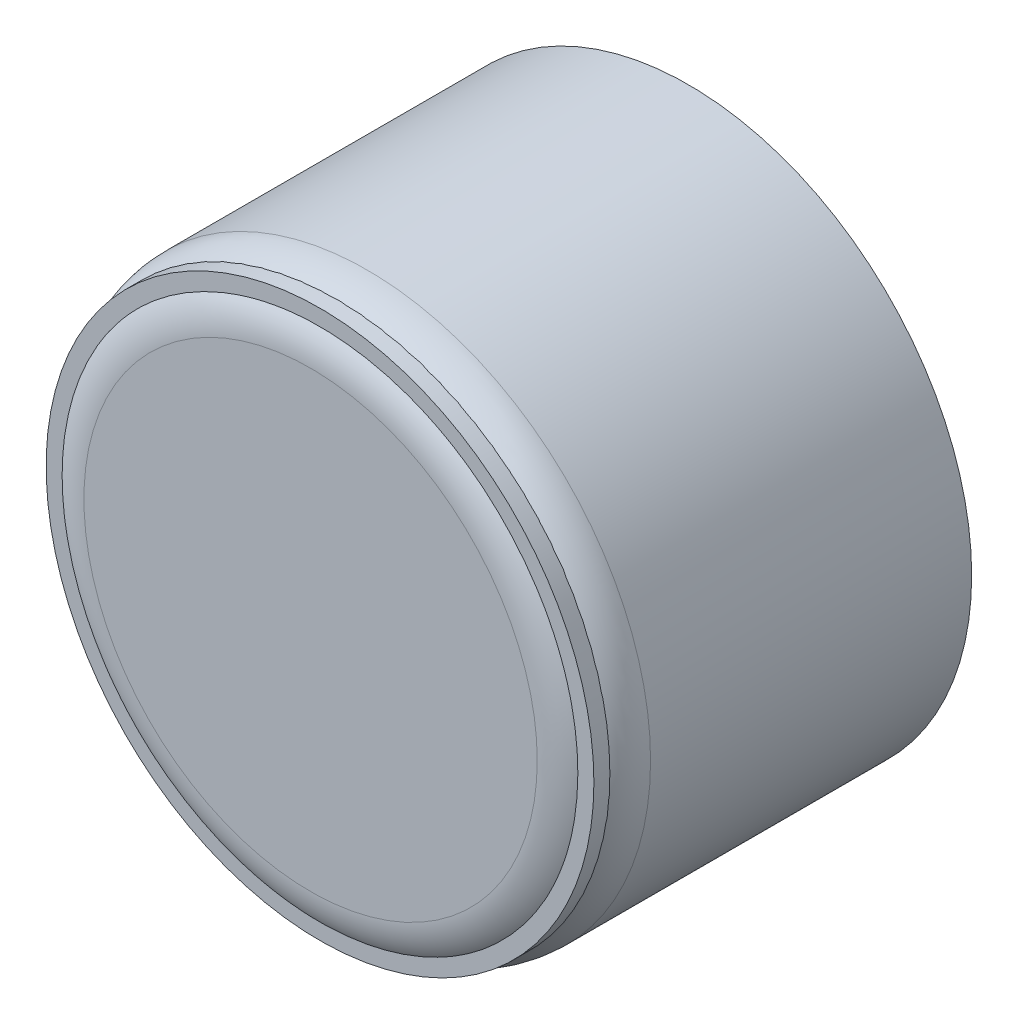
SolidWorks part; units mm, degrees
ref_plane "前视基准面" through (0, 0, 0) normal (0, 0, 1) x (1, 0, 0)
ref_plane "上视基准面" through (0, 0, 0) normal (0, 1, 0) x (1, 0, 0)
ref_plane "右视基准面" through (0, 0, 0) normal (1, 0, 0) x (0, 0, -1)
sketch "草图1" plane through (0, 0, 0) normal (0, 0, 1) x (1, 0, 0)
  circle A0 centre (0, 0) radius 15
extrude "凸台-拉伸1" add sketch "草图1" along normal blind 20
shell "抽壳1" thickness 0.5
fillet "圆角1" radius 3 1 edges at (15, 0, 20)
